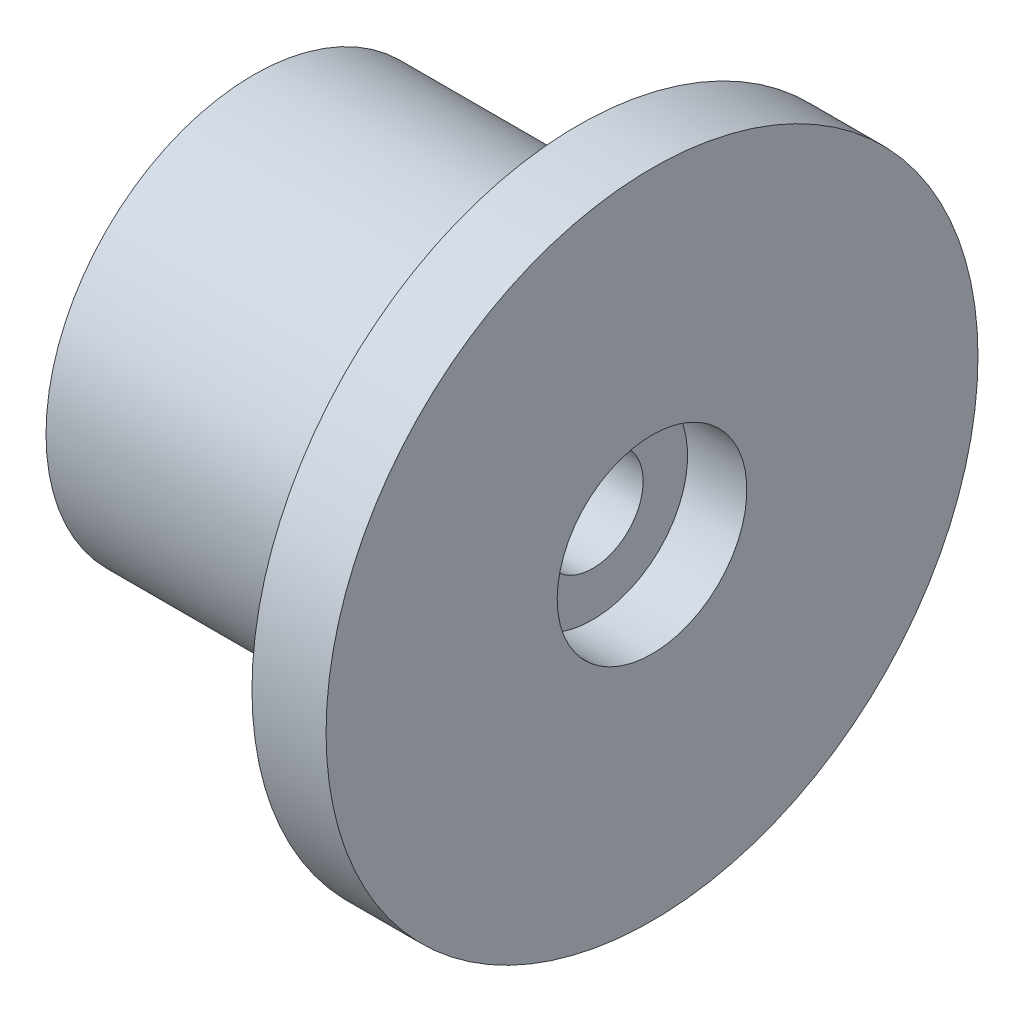
SolidWorks part; units mm, degrees
ref_plane "Front Plane" through (0, 0, 0) normal (0, 0, 1) x (1, 0, 0)
ref_plane "Top Plane" through (0, 0, 0) normal (0, 1, 0) x (1, 0, 0)
ref_plane "Right Plane" through (0, 0, 0) normal (1, 0, 0) x (0, 0, -1)
sketch "Sketch1" plane through (0, 0, 0) normal (0, 0, 1) x (1, 0, 0)
  line L0 (-5, 0) -> (20.95, 0) construction
  line L1 (0, 1.7) -> (0, 7)
  line L2 (0, 7) -> (10.95, 7)
  line L3 (10.95, 7) -> (10.95, 11)
  line L4 (10.95, 11) -> (13.45, 11)
  line L5 (13.45, 11) -> (13.45, 3.2)
  line L6 (13.45, 3.2) -> (11.45, 3.2)
  line L7 (11.45, 3.2) -> (11.45, 1.7)
  line L8 (11.45, 1.7) -> (0, 1.7)
revolve "Pin" add sketch "Sketch1" angle 360 about L0
